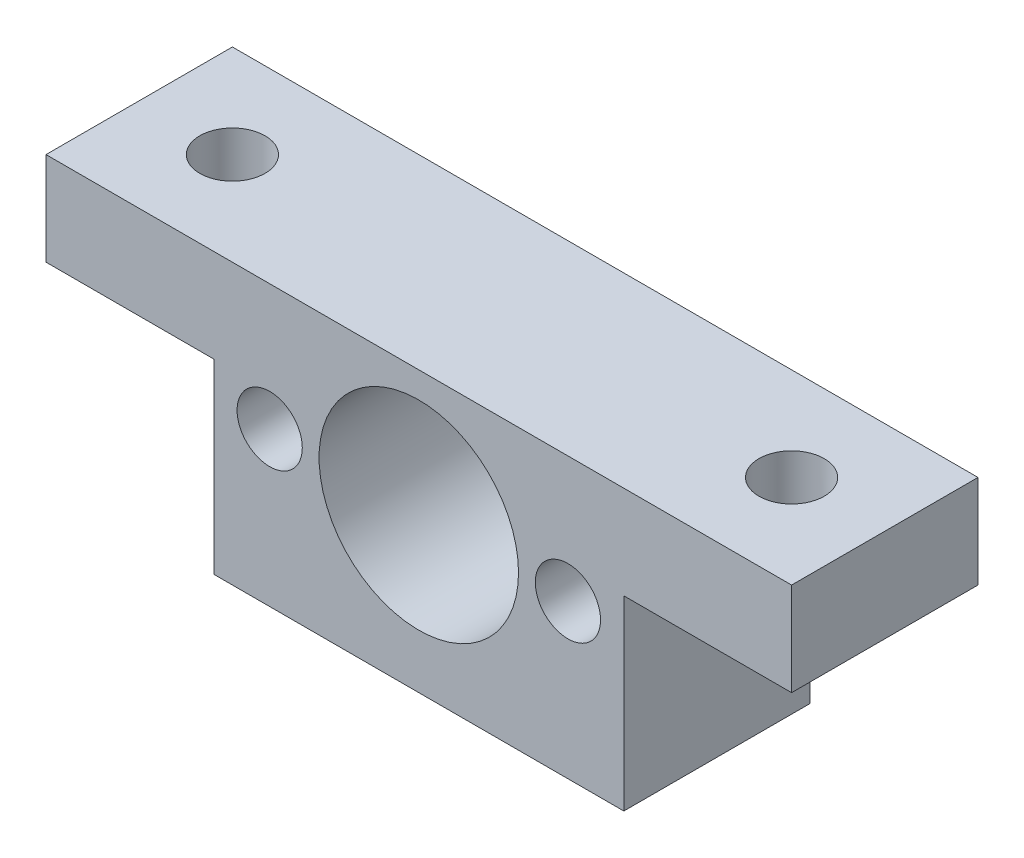
SolidWorks part; units mm, degrees
ref_plane "Plano frontal" through (0, 0, 0) normal (0, 0, 1) x (1, 0, 0)
ref_plane "Plano superior" through (0, 0, 0) normal (0, 1, 0) x (1, 0, 0)
ref_plane "Plano direito" through (0, 0, 0) normal (1, 0, 0) x (0, 0, -1)
sketch "Esboço1" plane through (0, 0, 0) normal (0, 0, 1) x (1, 0, 0)
  line L2 (-11, -5) -> (-11, -15)
  line L3 (-11, -15) -> (11, -15)
  line L4 (11, -5) -> (11, -15)
  line L7 (-20, 0) -> (-20, -5)
  line L8 (-20, -5) -> (-11, -5)
  line L9 (0, 0) -> (0, -15) construction
  line L10 (20, 0) -> (20, -5)
  line L11 (-20, 0) -> (20, 0)
  line L12 (20, -5) -> (11, -5)
  circle A0 centre (0, -6.75) radius 8 construction
  circle A1 centre (0, -6.75) radius 5.35
  circle A2 centre (-8, -6.75) radius 1.75
  circle A3 centre (8, -6.75) radius 1.75
  point P0 (0, 0)
  dimension "D5" = 15
  dimension "D6" = 10.7
  dimension "D3" = 6.75
  dimension "D7" = 16
  dimension "D8" = 3.5
  dimension "D1" = 40
  dimension "D2" = 22
  dimension "D4" = 5
extrude "Ressalto-extrusão1" add sketch "Esboço1" along normal blind 10
sketch "Esboço2" plane through (0, 0, 0) normal (0, 1, 0) x (1, 0, 0)
  line L0 (0, 0) -> (0, -10) construction
  line L1 (20, -10) -> (-20, -10) construction
  circle A0 centre (-15, -5) radius 1.75
  circle A1 centre (15, -5) radius 1.75
  point P8 (0, -5)
  dimension "D1" = 15
  dimension "D2" = 3.5
extrude "Corte-extrusão1" cut sketch "Esboço2" against normal blind 10
